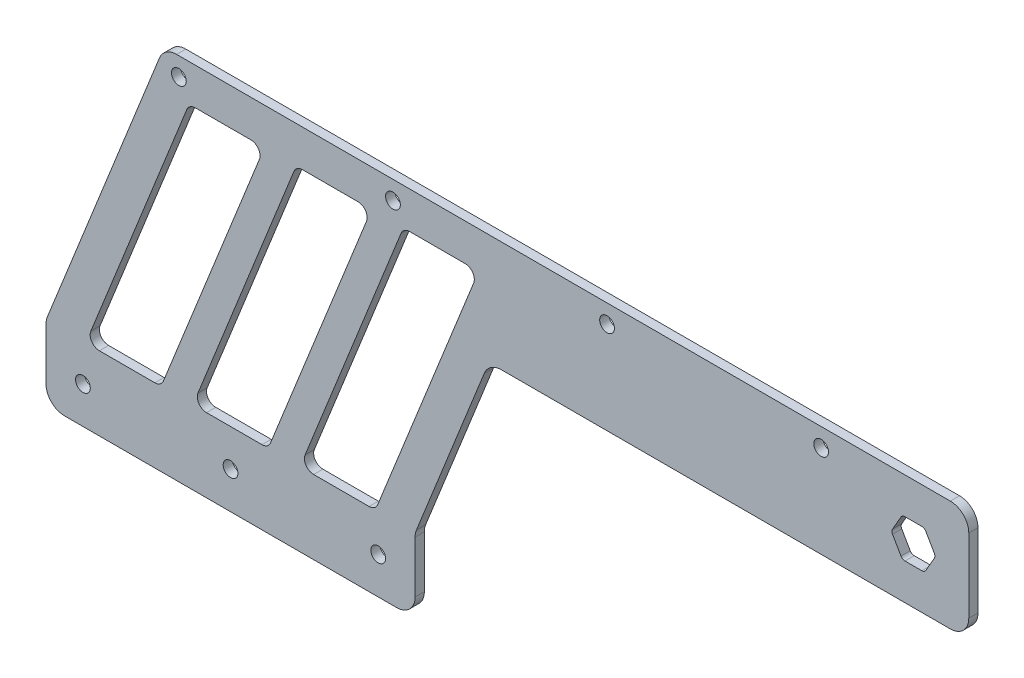
SolidWorks part; units mm, degrees
material "6061-T6 (SS)"
ref_plane "Front Plane" through (0, 0, 0) normal (0, 0, 1) x (1, 0, 0)
ref_plane "Top Plane" through (0, 0, 0) normal (0, 1, 0) x (1, 0, 0)
ref_plane "Right Plane" through (0, 0, 0) normal (1, 0, 0) x (0, 0, -1)
sketch "Sketch1" plane through (0, 0, 0) normal (0, 0, 1) x (1, 0, 0)
  line L0 (0, 25.4) -> (0, 0)
  line L1 (0, 0) -> (317.5, 0) construction
  line L2 (317.5, 0) -> (317.5, 25.4) construction
  line L3 (317.5, 25.4) -> (317.5, 127) construction
  line L4 (317.5, 127) -> (279.4, 127)
  line L5 (279.4, 127) -> (0, 25.4) construction
  line L6 (317.5, 127) -> (152.4, 127) construction
  line L7 (302.2628, 101.346) -> (306.0756, 107.95)
  line L8 (306.0756, 107.95) -> (302.2628, 114.554)
  line L9 (302.2628, 114.554) -> (294.6372, 114.554)
  line L10 (294.6372, 114.554) -> (290.8244, 107.95)
  line L11 (290.8244, 107.95) -> (294.6372, 101.346)
  line L12 (294.6372, 101.346) -> (302.2628, 101.346)
  line L13 (279.4, 127) -> (317.5, 127) construction
  line L14 (279.4, 127) -> (279.4, 88.9) construction
  line L15 (279.4, 88.9) -> (317.5, 88.9) construction
  line L16 (317.5, 127) -> (317.5, 88.9) construction
  line L17 (279.4, 127) -> (317.5, 88.9) construction
  line L18 (279.4, 88.9) -> (317.5, 127) construction
  line L19 (317.5, 88.9) -> (152.4, 88.9)
  line L21 (127, 0) -> (0, 0)
  line L22 (0, 25.4) -> (0, 127) construction
  line L23 (0, 127) -> (152.4, 127) construction
  line L24 (279.4, 127) -> (152.4, 127)
  line L25 (317.5, 88.9) -> (317.5, 127)
  line L26 (0, 25.4) -> (40.64, 127)
  line L27 (40.64, 127) -> (152.4, 127)
  line L28 (127, 0) -> (127, 25.4)
  line L29 (127, 25.4) -> (152.4, 88.9)
  circle A1 centre (298.45, 107.95) radius 6.604 construction
  circle A2 centre (12.7, 12.7) radius 2.54
  circle A3 centre (63.5, 12.7) radius 2.54
  circle A4 centre (114.3, 12.7) radius 2.54
  circle A5 centre (165.1, 12.7) radius 2.54 construction
  circle A6 centre (215.9, 12.7) radius 2.54 construction
  point P16 (298.45, 127)
  point P20 (298.45, 107.95)
  point P21 (0, 12.7)
  dimension "D4" = 13.208
  dimension "D6" = 5.08
  dimension "D1" = 25.4
  dimension "D2" = 152.4
  dimension "D3" = 38.1
  dimension "D5" = 101.6
  dimension "D7" = 12.7
  dimension "D9" = 50.8
  dimension "D13" = 165.1
  dimension "D14" = 127
  dimension "D8" = 5
extrude "Boss-Extrude1" add sketch "Sketch1" along normal blind 3.175
fillet "Fillet1" radius 6.35 8 edges at (40.64, 127, 1.5875) (317.5, 127, 1.5875) (317.5, 88.9, 1.5875) (152.4, 88.9, 1.5875) (127, 0, 1.5875) (0, 0, 1.5875) (0, 25.4, 1.5875) (127, 25.4, 1.5875)
sketch "Sketch2" plane through (0, 0, 3.175) normal (0, 0, 1) x (1, 0, 0)
  line L8 (13.6783, 25.4) -> (114.3393, 25.4)
  line L9 (6.35, 0) -> (120.65, 0) construction
  line L10 (45.069, 25.4) -> (80.629, 114.3)
  line L11 (81.931, 25.4) -> (117.491, 114.3)
  line L12 (30.9692, 68.6271) -> (56.8885, 68.6271) construction
  line L13 (67.8312, 68.6271) -> (93.7505, 68.6271) construction
  line L14 (49.562, 22.9542) -> (86.1003, 114.3)
  line L15 (86.424, 22.9542) -> (122.9623, 114.3)
  line L16 (304.8, 114.3) -> (49.2383, 114.3)
  line L17 (49.2383, 114.3) -> (12.7, 22.9542)
  line L18 (12.7, 22.9542) -> (12.7, 12.7)
  line L19 (12.7, 12.7) -> (114.3, 12.7)
  line L20 (114.3, 12.7) -> (114.3, 24.1771)
  line L21 (115.6625, 31.2521) -> (139.0117, 89.625)
  line L22 (156.6992, 101.6) -> (304.8, 101.6)
  line L23 (304.8, 101.6) -> (304.8, 114.3)
  line L24 (304.8, 114.3) -> (49.2383, 114.3)
  line L25 (49.2383, 114.3) -> (12.7, 22.9542)
  line L26 (12.7, 22.9542) -> (12.7, 12.7)
  line L27 (12.7, 12.7) -> (114.3, 12.7)
  line L28 (114.3, 12.7) -> (114.3, 24.1771)
  line L29 (115.6625, 31.2521) -> (139.0117, 89.625)
  line L30 (156.6992, 101.6) -> (304.8, 101.6)
  line L31 (304.8, 101.6) -> (304.8, 114.3)
  line L32 (39.5977, 25.4) -> (75.9123, 116.1867)
  line L33 (76.4597, 25.4) -> (112.7743, 116.1867)
  line L34 (49.7857, 23.5133) -> (85.3457, 112.4133) construction
  line L35 (86.6477, 23.5133) -> (122.2077, 112.4133) construction
  line L36 (77.2143, 27.2867) -> (112.7743, 116.1867) construction
  line L37 (40.3523, 27.2867) -> (75.9123, 116.1867) construction
  line L38 (104.6932, 68.6271) -> (130.6125, 68.6271) construction
  line L39 (139.0117, 89.625) -> (148.8817, 114.3)
  line L40 (115.6625, 31.2521) -> (112.9958, 24.5854)
  arc A16 (115.6625, 31.2521) -> (114.3, 24.1771) centre (133.35, 24.1771) ccw
  arc A17 (156.6992, 101.6) -> (139.0117, 89.625) centre (156.6992, 82.55) ccw
  arc A18 (115.6625, 31.2521) -> (114.3, 24.1771) centre (133.35, 24.1771) ccw
  arc A19 (156.6992, 101.6) -> (139.0117, 89.625) centre (156.6992, 82.55) ccw
  dimension "D2" = 25.4
  dimension "D1" = 12.7
  dimension "D3" = 5.08
  dimension "D4" = 5.08
extrude "Cut-Extrude1" cut sketch "Sketch2" against normal through all contours L8 L32 L24 L25 | L8 L33 L24 L14 | A18 L29 L39 L24 L15 L8
fillet "Fillet2" radius 3.175 12 edges at (13.6783, 25.4, 1.5875) (49.2383, 114.3, 1.5875) (75.1577, 114.3, 1.5875) (39.5977, 25.4, 1.5875) (50.5403, 25.4, 1.5875) (86.1003, 114.3, 1.5875) (112.0197, 114.3, 1.5875) (76.4597, 25.4, 1.5875) (87.4023, 25.4, 1.5875) (122.9623, 114.3, 1.5875) (148.8817, 114.3, 1.5875) (113.3217, 25.4, 1.5875)
sketch "Sketch3" plane through (0, 0, 3.175) normal (0, 0, 1) x (1, 0, 0)
  line L0 (38.1, 120.65) -> (317.5, 120.65) construction
  line L1 (39.0433, 123.0083) -> (0.4542, 26.5354) construction
  line L2 (317.5, 95.25) -> (317.5, 120.65) construction
  line L3 (70.4681, 114.3) -> (70.4681, 127) construction
  line L4 (311.15, 127) -> (44.9392, 127) construction
  circle A0 centre (45.72, 120.65) radius 2.54
  circle A1 centre (82.55, 120.65) radius 2.54 construction
  circle A2 centre (119.38, 120.65) radius 2.54
  circle A3 centre (156.21, 120.65) radius 2.54 construction
  circle A4 centre (193.04, 120.65) radius 2.54
  circle A5 centre (229.87, 120.65) radius 2.54 construction
  circle A6 centre (266.7, 120.65) radius 2.54
  point P13 (70.4681, 120.65)
  dimension "D1" = 5.08
  dimension "D2" = 7
  dimension "D3" = 36.83
  dimension "D4" = 7.62
extrude "Cut-Extrude2" cut sketch "Sketch3" against normal through all
fillet "Fillet3" radius 1.5875 6 edges at (302.2628, 101.346, 1.5875) (306.0756, 107.95, 1.5875) (302.2628, 114.554, 1.5875) (290.8244, 107.95, 1.5875) (294.6372, 101.346, 1.5875) (294.6372, 114.554, 1.5875)
sketch "Sketch4" plane through (0, 0, 0) normal (0, 0, 1) x (1, 0, 0)
  line L0 (-12.7, -6.8773) -> (-12.7, 49993.1227) construction
  line L1 (-12.7, -12.7) -> (49987.3, -12.7) construction
  line L2 (0, 24.1771) -> (0, 6.35) construction
  line L3 (6.35, 0) -> (120.65, 0) construction
  circle A0 centre (104.3721, 39.7655) radius 1.2334
  circle A1 centre (127.5559, 100.7688) radius 0.7672
  circle A2 centre (66.8244, 39.7655) radius 1.5147
  circle A3 centre (91.2638, 100.7688) radius 1.7855
  circle A4 centre (29.6203, 38.2507) radius 1.6208
  circle A5 centre (55.5047, 102.5543) radius 1.3156
  circle A6 centre (234.255, 94.0969) radius 2.3644
  circle A7 centre (145.525, 87.0304) radius 1.9646
  point P4 (-12.7, -12.7)
  dimension "D1" = 12.7
  dimension "D2" = 12.7
